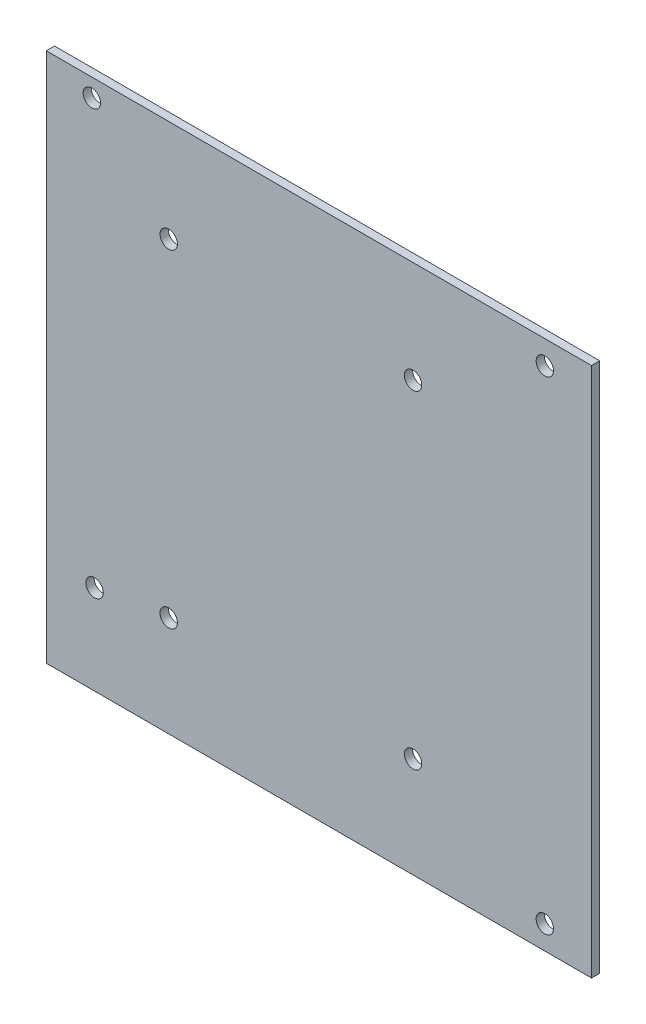
SolidWorks part; units mm, degrees
ref_plane "前视基准面" through (0, 0, 0) normal (0, 0, 1) x (1, 0, 0)
ref_plane "上视基准面" through (0, 0, 0) normal (0, 1, 0) x (1, 0, 0)
ref_plane "右视基准面" through (0, 0, 0) normal (1, 0, 0) x (0, 0, -1)
sketch "草图1" plane through (0, 0, 0) normal (0, 0, 1) x (1, 0, 0)
  line L0 (0, 4.42) -> (53.34, 4.42) construction
  line L1 (0, 0) -> (53.34, 0) construction
  line L2 (0, 0) -> (0, 68.58) construction
  line L3 (0, 68.58) -> (53.34, 68.58) construction
  line L4 (53.34, 0) -> (53.34, 68.58) construction
  line L5 (0, 64.16) -> (53.34, 64.16) construction
  line L6 (4.42, 68.58) -> (4.42, 0) construction
  line L7 (48.92, 68.58) -> (48.92, 0) construction
  line L9 (-17.88, 82.72) -> (81.42, 82.72)
  line L10 (-17.88, 82.72) -> (-17.88, -13.88)
  line L11 (-17.88, -13.88) -> (81.42, -13.88)
  line L12 (81.42, 82.72) -> (81.42, -13.88)
  circle A0 centre (48.92, 64.16) radius 1.585
  circle A1 centre (4.42, 64.16) radius 1.585
  circle A2 centre (4.42, 4.42) radius 1.585
  circle A3 centre (48.92, 4.42) radius 1.585
  circle A4 centre (-9.08, 2.42) radius 1.585
  circle A5 centre (72.92, -9.58) radius 1.585
  circle A6 centre (72.92, 78.42) radius 1.585
  circle A7 centre (-9.58, 79.42) radius 1.585
  dimension "D7" = 3.17
  dimension "D8" = 3.17
  dimension "D9" = 3.17
  dimension "D10" = 3.17
  dimension "D15" = 3.17
  dimension "D18" = 3.17
  dimension "D21" = 3.17
  dimension "D24" = 3.17
  dimension "D1" = 68.58
  dimension "D2" = 53.34
  dimension "D3" = 4.42
  dimension "D4" = 4.42
  dimension "D5" = 4.42
  dimension "D6" = 4.42
  dimension "D11" = 99.3
  dimension "D12" = 96.6
  dimension "D13" = 13.5
  dimension "D14" = 2
  dimension "D16" = 68.5
  dimension "D17" = 14
  dimension "D19" = 74
  dimension "D20" = 68.5
  dimension "D22" = 75
  dimension "D23" = 14
  dimension "D25" = 22.3
  dimension "D26" = 18.3
extrude "凸台-拉伸1" add sketch "草图1" along normal blind 1.5
